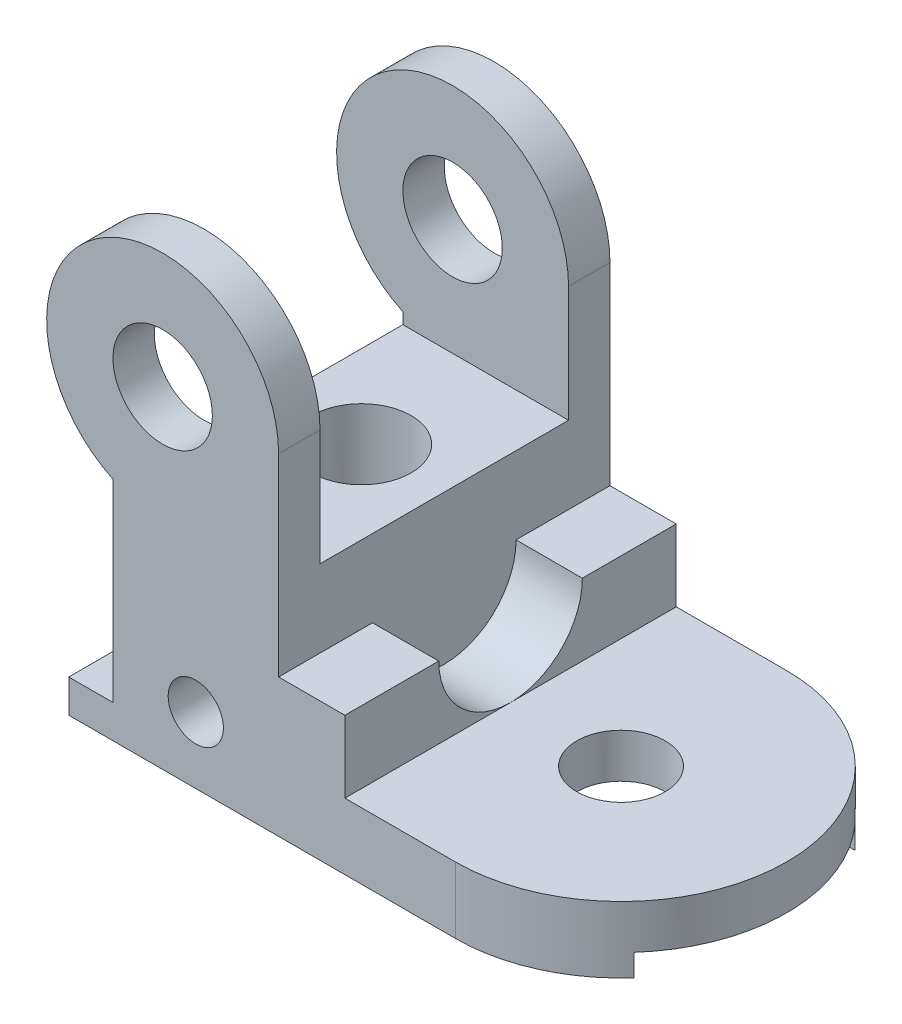
SolidWorks part; units mm, degrees
ref_plane "Front Plane" through (0, 0, 0) normal (0, 0, 1) x (1, 0, 0)
ref_plane "Top Plane" through (0, 0, 0) normal (0, 1, 0) x (1, 0, 0)
ref_plane "Right Plane" through (0, 0, 0) normal (1, 0, 0) x (0, 0, -1)
sketch "Sketch1" plane through (0, 0, 0) normal (0, 0, 1) x (1, 0, 0)
  line L0 (0, 0) -> (0, 6)
  line L1 (0, 6) -> (8, 6)
  line L2 (8, 6) -> (8, 41.0263)
  line L3 (0, 0) -> (100, 0)
  line L4 (100, 0) -> (100, 12)
  line L5 (100, 12) -> (50, 12)
  line L6 (50, 12) -> (50, 25)
  line L7 (50, 25) -> (38, 25)
  line L8 (38, 25) -> (38, 60)
  arc A0 (38, 60) -> (8, 41.0263) centre (17, 60) ccw
  circle A1 centre (17, 60) radius 9
  circle A2 centre (23, 12) radius 5
  dimension "D1" = 6
  dimension "D4" = 21
  dimension "D5" = 18
  dimension "D6" = 10
  dimension "D11" = 81
  dimension "D2" = 12
  dimension "D3" = 13
  dimension "D7" = 15
  dimension "D8" = 12
  dimension "D9" = 30
  dimension "D10" = 50
  dimension "D12" = 50
  dimension "D13" = 8
extrude "Boss-Extrude1" add sketch "Sketch1" along normal mid plane 60
sketch "Sketch2" plane through (38, 0, 0) normal (1, 0, 0) x (0, 0, -1)
  line L0 (30, 81) -> (-30, 81) construction
  line L1 (-22.5, 81) -> (22.5, 81)
  line L2 (-22.5, 81) -> (-22.5, 39)
  line L3 (-22.5, 39) -> (22.5, 39)
  line L4 (22.5, 81) -> (22.5, 39)
  line L5 (-30, 81) -> (-30, 41.0263) construction
  line L6 (30, 41.0263) -> (30, 81) construction
  dimension "D1" = 7.5
  dimension "D2" = 7.5
  dimension "D3" = 42
extrude "Cut-Extrude2" cut sketch "Sketch2" against normal through all
sketch "Sketch3" plane through (0, 12, 0) normal (0, 1, 0) x (1, 0, 0)
  line L0 (100, 30) -> (50, 30) construction
  line L1 (100, -30) -> (100, 30) construction
  line L5 (100, -30) -> (50, -30) construction
  circle A0 centre (70, 0) radius 30
  line M2 (100, 30) -> (50, 30)
  line M4 (50, -30) -> (100, -30)
  line M5 (100, -30) -> (100, 30)
extrude "Cut-Extrude3" cut sketch "Sketch3" against normal blind 60 contours A0 M5 M2 | A0 M4 M5
sketch "Sketch4" plane through (0, 39, 0) normal (0, 1, 0) x (1, 0, 0)
  line L0 (8, 22.5) -> (38, 22.5) construction
  line L1 (8, -30) -> (8, 30) construction
  circle A0 centre (23, 0) radius 9
  circle A1 centre (70, 0) radius 8
  arc A2 (70, -30) -> (70, 30) centre (70, 0) ccw construction
  point P4 (0, 0)
  point P10 (23, 22.5)
  point P13 (8, 0)
  dimension "D1" = 16
  dimension "D2" = 18
extrude "Cut-Extrude4" cut sketch "Sketch4" against normal through all both and the other way through all
sketch "Sketch5" plane through (50, 0, 0) normal (1, 0, 0) x (0, 0, -1)
  line L0 (-30, 25) -> (30, 25) construction
  line L1 (-30, 12) -> (30, 12) construction
  circle A0 centre (0, 25) radius 13
extrude "Cut-Extrude5" cut sketch "Sketch5" against normal up to surface (12 mm away) up to face at (38, 46, 0)
sketch "Sketch6" plane through (0, 0, 0) normal (-1, 0, 0) x (0, 0, 1)
  line L0 (30, 0) -> (-30, 0) construction
  line L1 (-20, 0) -> (20, 0)
  line L2 (-20, 0) -> (-20, 4)
  line L3 (-20, 4) -> (20, 4)
  line L4 (20, 0) -> (20, 4)
  point P6 (0, 4)
  dimension "D1" = 4
  dimension "D2" = 40
extrude "Cut-Extrude6" cut sketch "Sketch6" against normal through all
